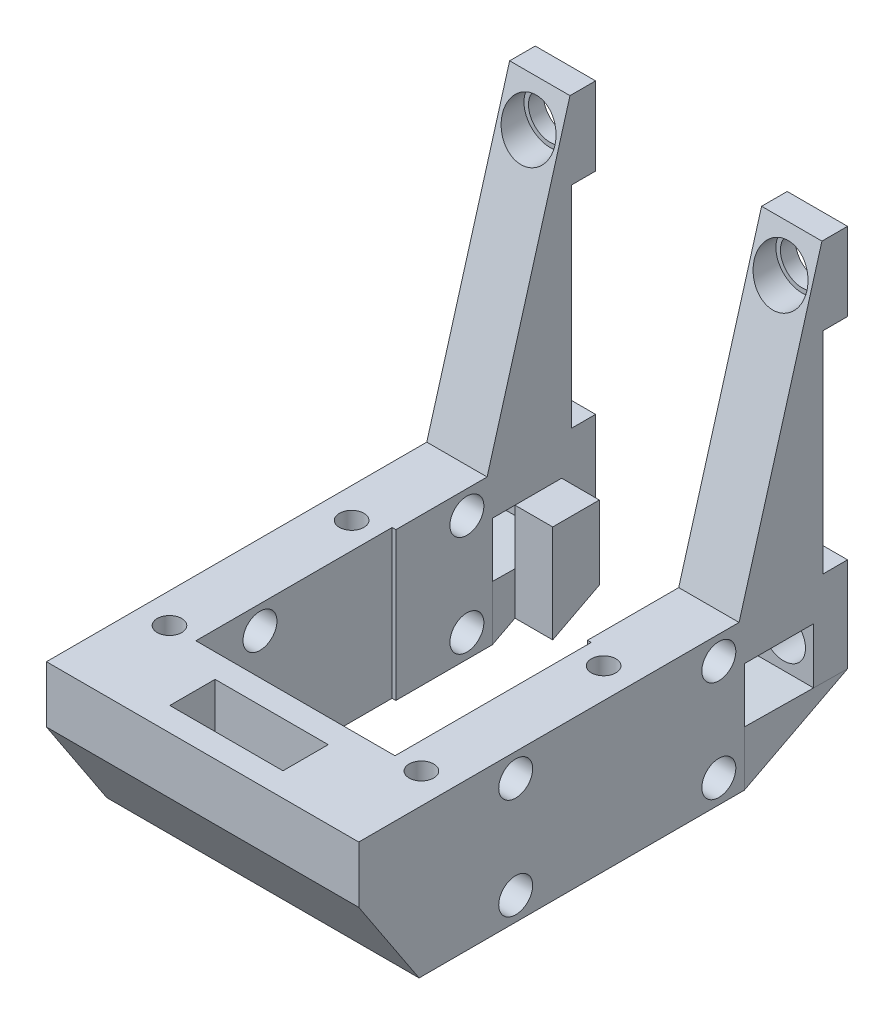
SolidWorks part; units mm, degrees
ref_plane "Front Plane" through (0, 0, 0) normal (0, 0, 1) x (1, 0, 0)
ref_plane "Top Plane" through (0, 0, 0) normal (0, 1, 0) x (1, 0, 0)
ref_plane "Right Plane" through (0, 0, 0) normal (1, 0, 0) x (0, 0, -1)
sketch "Sketch1" plane through (-474.147, -1016.1135, 5527.2949) normal (0, 0, 1) x (1, 0, 0)
  line L1 (211.6017, 683.0822) -> (219.1017, 683.0822)
  line L2 (211.6017, 683.0822) -> (211.6017, 675.5822)
  line L3 (211.6017, 675.5822) -> (219.1017, 675.5822)
  line L4 (219.1017, 683.0822) -> (219.1017, 675.5822)
  line L6 (237.0017, 683.0822) -> (237.0017, 675.5822)
  line L7 (237.0017, 675.5822) -> (229.5017, 675.5822)
  line L8 (229.5017, 683.0822) -> (229.5017, 675.5822)
  line L9 (237.0017, 683.0822) -> (229.5017, 683.0822)
  line L10 (237.0017, 718.5082) -> (229.5017, 718.5082)
  line L11 (237.0017, 711.0082) -> (237.0017, 718.5082)
  line L12 (229.5017, 711.0082) -> (229.5017, 718.5082)
  line L13 (237.0017, 711.0082) -> (229.5017, 711.0082)
  line L14 (211.6017, 718.5082) -> (219.1017, 718.5082)
  line L15 (211.6017, 711.0082) -> (211.6017, 718.5082)
  line L16 (219.1017, 711.0082) -> (219.1017, 718.5082)
  line L17 (211.6017, 711.0082) -> (219.1017, 711.0082)
  line L18 (219.1017, 675.5822) -> (229.5017, 675.5822) construction
  line L20 (237.0017, 683.0822) -> (237.0017, 711.0082) construction
  line L22 (211.6017, 683.0822) -> (211.6017, 711.0082) construction
  line L24 (219.1017, 718.5082) -> (229.5017, 718.5082) construction
  dimension "D1" = 237.1453
  dimension "D2" = 244.6453
  dimension "D3" = 255.0453
  dimension "D4" = 297.6053
  dimension "D5" = 333.0313
extrude "Boss-Extrude1" add sketch "Sketch1" along normal blind 5.5
sketch "Sketch2" plane through (0, 0, 5532.7949) normal (0, 0, 1) x (1, 0, 0)
  line L0 (-229.1453, -333.0313) -> (-229.1453, -340.5313)
  line L1 (-262.5453, -333.0313) -> (-270.5453, -333.0313)
  line L2 (-262.5453, -333.0313) -> (-262.5453, -340.5313)
  line L3 (-262.5453, -340.5313) -> (-270.5453, -340.5313)
  line L4 (-270.5453, -333.0313) -> (-270.5453, -340.5313)
  line L5 (-262.5453, -333.0313) -> (-262.5453, -340.5313) construction
  line L6 (-262.5453, -340.5313) -> (-255.0453, -340.5313) construction
  line L7 (-249.8453, -297.6053) -> (-249.8453, -340.5313) construction
  line L8 (-262.5453, -319.0683) -> (-237.1453, -319.0683) construction
  line L9 (-237.1453, -340.5313) -> (-229.1453, -340.5313)
  line L10 (-237.1453, -333.0313) -> (-237.1453, -340.5313)
  line L11 (-237.1453, -333.0313) -> (-229.1453, -333.0313)
  dimension "D1" = 7.5
  dimension "D2" = 8
  dimension "D3" = 12.7
  dimension "D4" = 21.463
extrude "Boss-Extrude2" add sketch "Sketch2" along normal blind 45 and the other way blind 5.5
sketch "Sketch3" plane through (0, 0, 5577.7949) normal (0, 0, 1) x (1, 0, 0)
  line L0 (-237.1453, -340.5313) -> (-229.1453, -340.5313) construction
  line L1 (-270.5453, -333.0313) -> (-229.1453, -333.0313)
  line L2 (-270.5453, -333.0313) -> (-270.5453, -340.5313)
  line L3 (-270.5453, -340.5313) -> (-229.1453, -340.5313)
  line L4 (-229.1453, -333.0313) -> (-229.1453, -340.5313)
  line L5 (-229.1453, -340.5313) -> (-229.1453, -333.0313) construction
extrude "Boss-Extrude3" add sketch "Sketch3" along normal blind 16
sketch "Sketch4" plane through (-262.5453, 0, 0) normal (-1, 0, 0) x (0, 0, 1)
  line L3 (5527.2949, -333.0313) -> (5527.2949, -294.744)
  line L4 (5527.2949, -294.744) -> (5532.3941, -294.744)
  line L5 (5527.2949, -297.6053) -> (5527.2949, -305.1053) construction
  line L6 (5532.3941, -294.744) -> (5543.3789, -333.0313)
  line L7 (5543.3789, -333.0313) -> (5527.2949, -333.0313)
  line L8 (5543.3789, -333.0313) -> (5581.4885, -333.0313) construction
  point P1 (0, 0)
  point P4 (0, 0)
  point P13 (5543.3789, -333.0313)
extrude "Boss-Extrude4" add sketch "Sketch4" along normal blind 8
ref_plane "Plane1" through (-249.8453, 0, 0) normal (-1, 0, 0) x (0, 0, 1)
mirror "Mirror1" about plane through (-249.8453, 0, 0) normal (-1, 0, 0) of "Boss-Extrude2", "Boss-Extrude4"
sketch "Sketch5" plane through (0, 0, 5532.7949) normal (0, 0, 1) x (1, 0, 0)
  line L0 (-258.7953, -297.6053) -> (-258.7953, -305.1053) construction
  line L1 (-255.0453, -297.6053) -> (-262.5453, -297.6053) construction
  line L2 (-262.5453, -305.1053) -> (-255.0453, -305.1053) construction
  line L3 (-255.0453, -301.3553) -> (-262.5453, -301.3553) construction
  line L4 (-255.0453, -305.1053) -> (-255.0453, -297.6053) construction
  line L5 (-262.5453, -297.6053) -> (-262.5453, -305.1053) construction
  line L6 (-255.0453, -297.6053) -> (-244.6453, -297.6053) construction
  line L7 (-249.8453, -297.6053) -> (-249.8453, -305.1053) construction
  line L8 (-255.0453, -305.1053) -> (-244.6453, -305.1053) construction
  line L9 (-255.0453, -340.5313) -> (-244.6453, -340.5313) construction
  line L10 (-255.0453, -333.0313) -> (-244.6453, -333.0313) construction
  line L11 (-249.8453, -305.1053) -> (-249.8453, -333.0313) construction
  line L12 (-255.0453, -333.0313) -> (-255.0453, -305.1053) construction
  line L13 (-249.8453, -319.0683) -> (-255.0453, -319.0683) construction
  line L14 (-244.6453, -301.3553) -> (-237.1453, -301.3553) construction
  line L15 (-240.8953, -297.6053) -> (-240.8953, -305.1053) construction
  line L16 (-244.6453, -336.7813) -> (-237.1453, -336.7813) construction
  line L17 (-240.8953, -340.5313) -> (-240.8953, -333.0313) construction
  line L18 (-258.7953, -340.5313) -> (-258.7953, -333.0313) construction
  line L19 (-255.0453, -336.7813) -> (-262.5453, -336.7813) construction
  circle A0 centre (-258.7953, -301.3553) radius 2.5
  circle A1 centre (-240.8953, -301.3553) radius 2.5
  circle A2 centre (-240.8953, -336.7813) radius 2.5
  circle A3 centre (-258.7953, -336.7813) radius 2.5
  dimension "D1" = 5
extrude "Cut-Extrude1" cut sketch "Sketch5" against normal blind 8
sketch "Sketch6" plane through (-270.5453, 0, 0) normal (-1, 0, 0) x (0, 0, 1)
  line L0 (5527.2949, -340.5313) -> (5593.7949, -340.5313) construction
  line L1 (5539.6853, -340.5313) -> (5577.7949, -340.5313)
  line L2 (5539.6853, -340.5313) -> (5539.6853, -352.6436)
  line L3 (5539.6853, -352.6436) -> (5577.7949, -352.6436)
  line L4 (5577.7949, -340.5313) -> (5577.7949, -352.6436)
extrude "Boss-Extrude6" add sketch "Sketch6" against normal blind 8
ref_plane "Plane2" through (-249.8453, 0, 0) normal (-1, 0, 0) x (0, 0, 1)
mirror "Mirror2" about plane through (-249.8453, 0, 0) normal (-1, 0, 0) of "Boss-Extrude6"
sketch "Sketch9" plane through (0, 0, 5577.7949) normal (0, 0, 1) x (1, 0, 0)
  line L0 (-262.5453, -352.6436) -> (-270.5453, -352.6436) construction
  line L1 (-270.5453, -352.6436) -> (-229.1453, -352.6436)
  line L2 (-270.5453, -352.6436) -> (-270.5453, -340.5313)
  line L3 (-270.5453, -340.5313) -> (-229.1453, -340.5313)
  line L4 (-229.1453, -352.6436) -> (-229.1453, -340.5313)
  line L5 (-270.5453, -352.6436) -> (-270.5453, -340.5313) construction
  line L6 (-270.5453, -340.5313) -> (-229.1453, -340.5313) construction
extrude "Boss-Extrude7" add sketch "Sketch9" along normal blind 8
sketch "Sketch10" plane through (-270.5453, 0, 0) normal (-1, 0, 0) x (0, 0, 1)
  line L0 (5572.9896, -336.1377) -> (5572.9896, -333.0313) construction
  line L1 (5543.3789, -333.0313) -> (5593.7949, -333.0313) construction
  line L2 (5572.9896, -352.6436) -> (5572.9896, -349.5373) construction
  line L3 (5539.6853, -352.6436) -> (5585.7949, -352.6436) construction
  circle A4 centre (5546.0612, -349.5373) radius 2.25
  circle A5 centre (5572.9896, -349.5373) radius 2.25
  circle A6 centre (5546.0612, -336.1377) radius 2.25
  circle A7 centre (5572.9896, -336.1377) radius 2.25
  dimension "D1" = 4.5
  dimension "D2" = 13.6671
  dimension "D3" = 40.5955
  dimension "D4" = 3.1064
extrude "Cut-Extrude2" cut sketch "Sketch10" against normal through all
sketch "Sketch11" plane through (-270.5453, 0, 0) normal (-1, 0, 0) x (0, 0, 1)
  line L0 (5527.2949, -340.3725) -> (5539.6853, -352.6436)
  line L1 (5527.2949, -294.744) -> (5527.2949, -340.5313) construction
  line L2 (5539.6853, -340.5313) -> (5539.6853, -352.6436) construction
  line L3 (5539.6853, -352.6436) -> (5539.6853, -340.5313)
  line L4 (5527.2949, -340.5313) -> (5539.6853, -340.5313) construction
  line L5 (5539.6853, -340.5313) -> (5527.2949, -340.3725)
  line L7 (5539.6853, -352.6436) -> (5585.7949, -352.6436) construction
  dimension "D1" = 12.2712
extrude "Boss-Extrude8" add sketch "Sketch11" against normal blind 8
sketch "Sketch12" plane through (-229.1453, 0, 0) normal (1, 0, 0) x (0, 0, -1)
  line L0 (-5539.6853, -352.6436) -> (-5531.2403, -340.5313)
  line L1 (-5539.6853, -340.5313) -> (-5539.6853, -352.6436) construction
  line L2 (-5539.6853, -340.5313) -> (-5527.2949, -340.5313) construction
  line L3 (-5531.2403, -340.5313) -> (-5539.6853, -340.5313)
  line L4 (-5539.6853, -340.5313) -> (-5539.6853, -352.6436)
  line L5 (-5531.2437, -340.8533) -> (-5530.8232, -301.2163) construction
  point P6 (-5527.5467, -340.5313)
extrude "Boss-Extrude9" add sketch "Sketch12" against normal blind 8
sketch "Sketch13" plane through (-270.5453, 0, 0) normal (-1, 0, 0) x (0, 0, 1)
  line L0 (5527.8316, -294.744) -> (5527.8316, -302.244) construction
  line L1 (5532.3941, -294.744) -> (5527.2949, -294.744) construction
  line L2 (5527.8316, -340.5313) -> (5527.8316, -333.0313) construction
  line L3 (5527.2949, -294.744) -> (5527.2949, -340.5313) construction
  line L4 (5527.2949, -333.0313) -> (5532.2204, -333.0313)
  line L5 (5527.2949, -333.0313) -> (5527.2949, -305.1053)
  line L6 (5527.2949, -305.1053) -> (5532.2204, -305.1053)
  line L7 (5532.2204, -333.0313) -> (5532.2204, -305.1053)
  point P12 (5532.2204, -333.0313)
  dimension "D1" = 7.5
  dimension "D2" = 7.5
extrude "Cut-Extrude3" cut sketch "Sketch13" against normal through all
sketch "Sketch14" plane through (-270.5453, 0, 0) normal (-1, 0, 0) x (0, 0, 1)
  line L0 (5585.7949, -352.6436) -> (5593.7949, -340.5313)
  line L1 (5585.7949, -340.5313) -> (5585.7949, -352.6436) construction
  line L2 (5585.7949, -340.5313) -> (5593.7949, -340.5313) construction
  line L3 (5593.7949, -340.5313) -> (5585.7949, -340.5313)
  line L4 (5585.7949, -340.5313) -> (5585.7949, -352.6436)
extrude "Boss-Extrude10" add sketch "Sketch14" against normal blind 41.4
sketch "Sketch16" plane through (0, -333.0313, 0) normal (0, 1, 0) x (1, 0, 0)
  line L1 (-263.0453, -5555.4748) -> (-236.6453, -5555.4748)
  line L2 (-263.0453, -5555.4748) -> (-263.0453, -5581.4885)
  line L3 (-263.0453, -5581.4885) -> (-236.6453, -5581.4885)
  line L4 (-236.6453, -5555.4748) -> (-236.6453, -5581.4885)
  line L5 (-263.0453, -5566.5853) -> (-270.5453, -5566.5853) construction
  line L6 (-270.5453, -5543.3789) -> (-270.5453, -5593.7949) construction
  line L7 (-236.6453, -5567.7425) -> (-229.1453, -5567.7425) construction
  line L8 (-229.1453, -5593.7949) -> (-229.1453, -5543.3789) construction
  line L10 (-229.1453, -5543.3789) -> (-237.1453, -5543.3789) construction
  dimension "D1" = 7.5
  dimension "D2" = 12.0959
  dimension "D3" = 23.2064
  dimension "D4" = 24.3636
  dimension "D5" = 38.1096
extrude "Cut-Extrude5" cut sketch "Sketch16" against normal through all
sketch "Sketch17" plane through (0, -297.6053, 0) normal (0, 1, 0) x (1, 0, 0)
  line L1 (-237.1453, -5527.2949) -> (-262.5453, -5527.2949)
  line L2 (-237.1453, -5527.2949) -> (-237.1453, -5532.7949)
  line L3 (-237.1453, -5532.7949) -> (-262.5453, -5532.7949)
  line L4 (-262.5453, -5527.2949) -> (-262.5453, -5532.7949)
extrude "Cut-Extrude6" cut sketch "Sketch17" against normal blind 50
sketch "Sketch18" plane through (0, -294.744, 0) normal (0, 1, 0) x (1, 0, 0)
  line L1 (-270.5453, -5527.2949) -> (-229.1453, -5527.2949)
  line L2 (-270.5453, -5527.2949) -> (-270.5453, -5528.9982)
  line L3 (-270.5453, -5528.9982) -> (-229.1453, -5528.9982)
  line L4 (-229.1453, -5527.2949) -> (-229.1453, -5528.9982)
  line L5 (-229.1453, -5532.3941) -> (-229.1453, -5527.2949) construction
  point P5 (-229.1453, -5528.9982)
  point P7 (0, 0)
extrude "Cut-Extrude7" cut sketch "Sketch18" against normal blind 50
sketch "Sketch19" plane through (0, 0, 5528.9982) normal (0, 0, -1) x (-1, 0, 0)
  line L0 (233.1453, -294.744) -> (233.1453, -305.1053) construction
  line L1 (237.1453, -294.744) -> (229.1453, -294.744) construction
  line L2 (237.1453, -305.1053) -> (229.1453, -305.1053) construction
  line L3 (229.1453, -299.9246) -> (237.1453, -299.9246) construction
  line L4 (229.1453, -305.1053) -> (229.1453, -294.744) construction
  line L5 (237.1453, -305.1053) -> (237.1453, -294.744) construction
  circle A0 centre (233.1453, -299.9246) radius 2.9
  dimension "D1" = 5.8
extrude "Cut-Extrude8" cut sketch "Sketch19" against normal blind 50
ref_plane "Plane3" through (0, 0, 5538.9982) normal (0, 0, -1) x (-1, 0, 0)
sketch "Sketch20" plane through (0, 0, 5538.9982) normal (0, 0, -1) x (-1, 0, 0)
  circle A1 centre (233.1453, -299.9246) radius 3.5
  dimension "D1" = 7
extrude "Cut-Extrude9" cut sketch "Sketch20" along normal blind 8
ref_plane "Plane4" through (-249.8453, 0, 0) normal (-1, 0, 0) x (0, 0, 1)
mirror "Mirror3" about plane through (-249.8453, 0, 0) normal (-1, 0, 0) of "Cut-Extrude9", "Cut-Extrude8"
ref_plane "Plane5" through (0, -319.0683, 0) normal (0, 1, 0) x (1, 0, 0)
sketch "Sketch21" plane through (-270.5453, 0, 0) normal (-1, 0, 0) x (0, 0, 1)
  line L0 (5528.9982, -342.0594) -> (5528.9982, -333.0313) construction
  line L1 (5528.9982, -338.1154) -> (5539.6853, -338.1154)
  line L2 (5528.9982, -338.1154) -> (5528.9982, -352.6436)
  line L3 (5528.9982, -352.6436) -> (5539.6853, -352.6436)
  line L4 (5539.6853, -338.1154) -> (5539.6853, -352.6436)
extrude "Cut-Extrude10" cut sketch "Sketch21" against normal blind 55
sketch "Sketch22" plane through (0, -338.1154, 0) normal (0, -1, 0) x (1, 0, 0)
  line L0 (-262.5453, 5528.9982) -> (-262.5453, 5539.6853) construction
  line L1 (-270.5453, 5528.9982) -> (-262.5453, 5528.9982)
  line L2 (-270.5453, 5528.9982) -> (-270.5453, 5533.4982)
  line L3 (-270.5453, 5533.4982) -> (-262.5453, 5533.4982)
  line L4 (-262.5453, 5528.9982) -> (-262.5453, 5533.4982)
  dimension "D1" = 4.5
extrude "Boss-Extrude11" add sketch "Sketch22" along normal blind 7.4279
mirror "Mirror5" about plane through (-249.8453, 0, 0) normal (-1, 0, 0) of "Boss-Extrude11"
sketch "Sketch23" plane through (0, 0, 5528.9982) normal (0, 0, -1) x (-1, 0, 0)
  circle A0 centre (233.1189, -341.4699) radius 2.9
  dimension "D1" = 5.8
extrude "Cut-Extrude11" cut sketch "Sketch23" against normal blind 5
ref_plane "Plane6" through (-270.5453, -338.1154, 5539.6853) normal (0, 1, 0) x (1, 0, 0)
sketch "Sketch25" plane through (-262.5453, 0, 0) normal (1, 0, 0) x (0, 0, -1)
  line L0 (-5539.6853, -338.1154) -> (-5533.4982, -338.1154) construction
  line L1 (-5539.6853, -352.6436) -> (-5533.4982, -352.6436)
  line L2 (-5539.6853, -352.6436) -> (-5539.6853, -338.1154)
  line L3 (-5539.6853, -338.1154) -> (-5533.4982, -338.1154)
  line L4 (-5533.4982, -352.6436) -> (-5533.4982, -338.1154)
  point P6 (-5539.1835, -338.1154)
  point P9 (-5539.6853, -338.1154)
extrude "Boss-Extrude12" add sketch "Sketch25" along normal blind 5 separate body
sketch "Sketch26" plane through (-270.5453, 0, 0) normal (-1, 0, 0) x (0, 0, 1)
  line L0 (5539.6853, -352.6436) -> (5585.7949, -352.6436) construction
  line L1 (5539.6853, -338.1154) -> (5542.6853, -338.1154)
  line L2 (5539.6853, -338.1154) -> (5539.6853, -352.6436)
  line L3 (5539.6853, -352.6436) -> (5542.6853, -352.6436)
  line L4 (5542.6853, -338.1154) -> (5542.6853, -352.6436)
  point P5 (5542.6853, -352.6436)
  dimension "D1" = 3
extrude "Cut-Extrude12" cut sketch "Sketch26" against normal through all
sketch "Sketch27" plane through (-270.5453, 0, 0) normal (-1, 0, 0) x (0, 0, 1)
  line L0 (5542.6853, -352.6436) -> (5528.9982, -345.5433)
  line L1 (5528.9982, -345.5433) -> (5542.6853, -345.3795)
  line L2 (5542.6853, -352.6436) -> (5542.6853, -338.1154) construction
  line L3 (5542.6853, -345.3795) -> (5542.6853, -352.6436)
extrude "Boss-Extrude15" add sketch "Sketch27" against normal up to surface (8 mm away) separate body up to face at (-262.5453, -345.3795, 5536.5917)
mirror "Mirror6" about plane through (-249.8453, 0, 0) normal (-1, 0, 0) of "Cut-Extrude11"
sketch "Sketch28" plane through (-262.5453, 0, 0) normal (-1, 0, 0) x (0, 0, 1)
  line L0 (5533.4982, -347.8777) -> (5539.6853, -351.0873)
  line L1 (5542.6853, -352.6436) -> (5528.9982, -345.5433) construction
  line L2 (5533.4982, -352.6436) -> (5533.4982, -338.1154) construction
  line L3 (5539.6853, -338.1154) -> (5539.6853, -352.6436) construction
  line L4 (5539.6853, -351.0873) -> (5543.3789, -359.5636)
  line L5 (5543.3789, -377.1583) -> (5543.3789, -333.0313) construction
  line L6 (5543.3789, -359.5636) -> (5533.2622, -359.5636)
  line L7 (5533.2622, -359.5636) -> (5533.4982, -347.8777)
extrude "Cut-Extrude13" cut sketch "Sketch28" against normal through all
mirror "Mirror11" about plane through (-249.8453, 0, 0) normal (-1, 0, 0) of bodies 170 168
sketch "Sketch29" plane through (0, -333.0313, 0) normal (0, 1, 0) x (1, 0, 0)
  line L0 (-249.8453, -5593.7949) -> (-249.8453, -5581.4885) construction
  line L1 (-229.1453, -5593.7949) -> (-270.5453, -5593.7949) construction
  line L2 (-263.0453, -5581.4885) -> (-236.6453, -5581.4885) construction
  line L4 (-242.3453, -5584.6417) -> (-257.3453, -5584.6417)
  line L5 (-242.3453, -5584.6417) -> (-242.3453, -5590.6417)
  line L6 (-242.3453, -5590.6417) -> (-257.3453, -5590.6417)
  line L7 (-257.3453, -5584.6417) -> (-257.3453, -5590.6417)
  line L8 (-242.3453, -5584.6417) -> (-257.3453, -5590.6417) construction
  line L9 (-242.3453, -5590.6417) -> (-257.3453, -5584.6417) construction
  point P6 (-249.8453, -5587.6417)
  dimension "D1" = 15
  dimension "D2" = 6
extrude "Cut-Extrude14" cut sketch "Sketch29" against normal blind 10
sketch "Sketch30" plane through (0, -333.0313, 0) normal (0, 1, 0) x (1, 0, 0)
  line L0 (-270.5453, -5557.3356) -> (-266.5453, -5557.3356) construction
  line L1 (-270.5453, -5543.3789) -> (-270.5453, -5593.7949) construction
  line L2 (-266.5453, -5543.3789) -> (-266.5453, -5565.5846) construction
  line L3 (-270.5453, -5543.3789) -> (-262.5453, -5543.3789) construction
  circle A0 centre (-266.5453, -5557.3356) radius 1.625
  dimension "D1" = 3.25
extrude "Cut-Extrude15" cut sketch "Sketch30" against normal blind 10
sketch "Sketch31" plane through (0, -333.0313, 0) normal (0, 1, 0) x (1, 0, 0)
  line L0 (-229.1453, -5581.4885) -> (-234.0224, -5581.4885) construction
  line L1 (-229.1453, -5593.7949) -> (-229.1453, -5543.3789) construction
  line L2 (-263.0453, -5581.4885) -> (-236.6453, -5581.4885) construction
  line L3 (-233.1453, -5543.3789) -> (-233.1453, -5581.4885) construction
  line L4 (-229.1453, -5543.3789) -> (-237.1453, -5543.3789) construction
  circle A0 centre (-233.1453, -5581.4885) radius 1.625
  dimension "D1" = 3.25
extrude "Cut-Extrude16" cut sketch "Sketch31" against normal blind 10
ref_plane "Plane7" through (-249.8453, 0, 0) normal (-1, 0, 0) x (0, 0, 1)
mirror "Mirror12" about plane through (-249.8453, 0, 0) normal (-1, 0, 0) of "Cut-Extrude16", "Cut-Extrude15"
